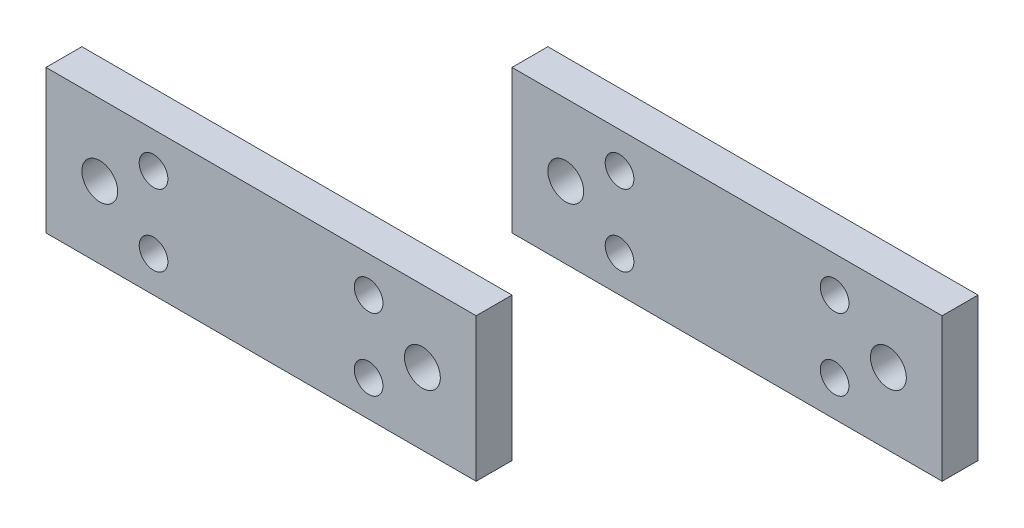
SolidWorks part; units mm, degrees
ref_plane "Front Plane" through (0, 0, 0) normal (0, 0, 1) x (1, 0, 0)
ref_plane "Top Plane" through (0, 0, 0) normal (0, 1, 0) x (1, 0, 0)
ref_plane "Right Plane" through (0, 0, 0) normal (1, 0, 0) x (0, 0, -1)
sketch "Sketch1" plane through (0, 0, 0) normal (0, 0, 1) x (1, 0, 0)
  line L0 (17.5, 10.5204) -> (17.5, 2.5204) construction
  line L1 (-20.5, -2.4796) -> (3.5, -2.4796)
  line L2 (-20.5, -2.4796) -> (-20.5, -10.4796)
  line L3 (-20.5, -10.4796) -> (3.5, -10.4796)
  line L4 (3.5, -2.4796) -> (3.5, -10.4796)
  line L5 (5.5, 10.5204) -> (29.5, 10.5204)
  line L6 (5.5, 10.5204) -> (5.5, 2.5204)
  line L7 (5.5, 2.5204) -> (29.5, 2.5204)
  line L8 (29.5, 10.5204) -> (29.5, 2.5204)
  line L9 (17.5, 6.5204) -> (5.5, 6.5204) construction
  line L10 (-8.5, -10.4796) -> (-8.5, -2.4796) construction
  line L11 (-8.5, -6.4796) -> (3.5, -6.4796) construction
  circle A0 centre (11.5, 8.5204) radius 0.8
  circle A1 centre (8.5, 6.5204) radius 1
  circle A2 centre (11.5, 4.5204) radius 0.8
  circle A3 centre (23.5, 4.5204) radius 0.8
  circle A4 centre (26.5, 6.5204) radius 1
  circle A5 centre (23.5, 8.5204) radius 0.8
  circle A6 centre (0.5, -6.4796) radius 1
  circle A7 centre (-14.5, -4.4796) radius 0.8
  circle A8 centre (-2.5, -8.4796) radius 0.8
  circle A9 centre (-2.5, -4.4796) radius 0.8
  circle A10 centre (-17.5, -6.4796) radius 1
  circle A11 centre (-14.5, -8.4796) radius 0.8
  dimension "D7" = 1.6
  dimension "D8" = 9
  dimension "D1" = 8
  dimension "D2" = 8
  dimension "D3" = 2
  dimension "D4" = 24
  dimension "D5" = 24
  dimension "D6" = 5
  dimension "D9" = 6
  dimension "D10" = 2
  dimension "D11" = 9
  dimension "D12" = 6
  dimension "D13" = 2
  dimension "D14" = 12
extrude "Boss-Extrude1" add sketch "Sketch1" along normal blind 2
